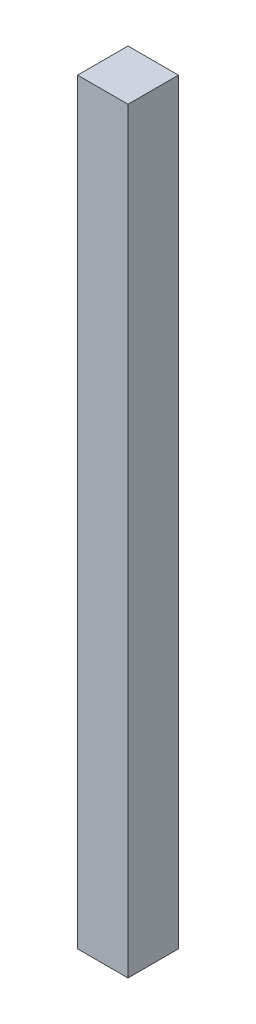
SolidWorks part; units mm, degrees
ref_plane "Front Plane" through (0, 0, 0) normal (0, 0, 1) x (1, 0, 0)
ref_plane "Top Plane" through (0, 0, 0) normal (0, 1, 0) x (1, 0, 0)
ref_plane "Right Plane" through (0, 0, 0) normal (1, 0, 0) x (0, 0, -1)
sketch "Sketch1" plane through (0, 0, 0) normal (0, 1, 0) x (1, 0, 0)
  line L1 (0, 0) -> (20, 0)
  line L2 (0, 0) -> (0, -20)
  line L3 (0, -20) -> (20, -20)
  line L4 (20, 0) -> (20, -20)
extrude "Boss-Extrude1" add sketch "Sketch1" along normal blind 300
